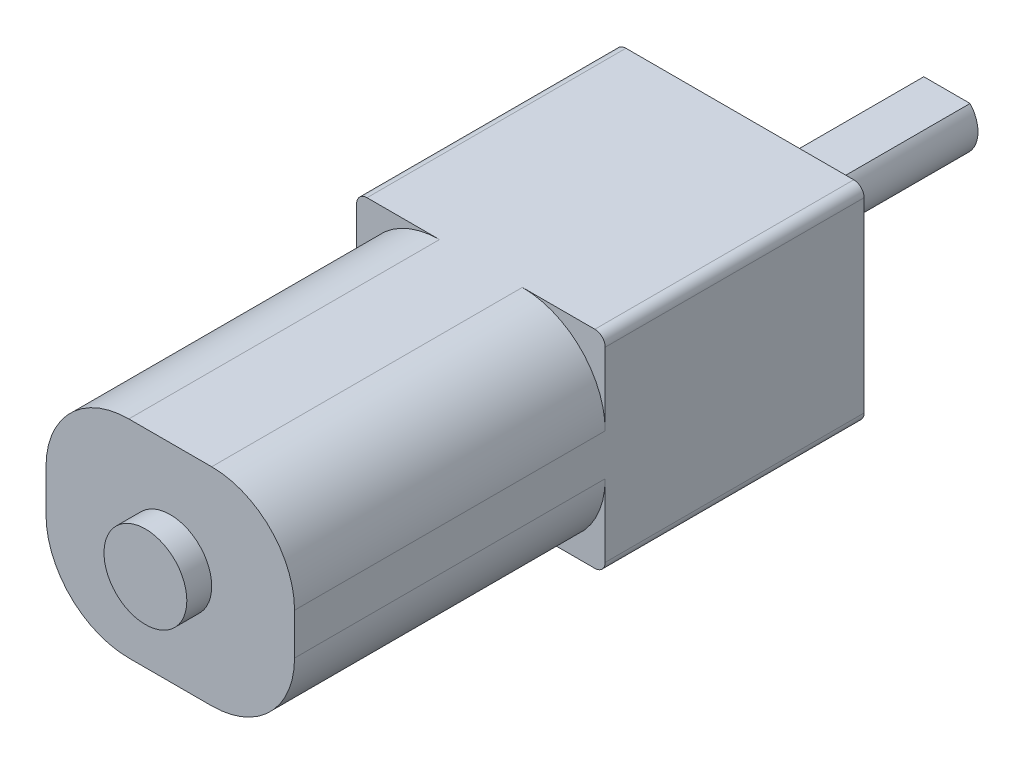
SolidWorks part; units mm, degrees
ref_plane "Front Plane" through (0, 0, 0) normal (0, 0, 1) x (1, 0, 0)
ref_plane "Top Plane" through (0, 0, 0) normal (0, 1, 0) x (1, 0, 0)
ref_plane "Right Plane" through (0, 0, 0) normal (1, 0, 0) x (0, 0, -1)
sketch "Sketch1" plane through (0, 0, 0) normal (0, 0, 1) x (1, 0, 0)
  line L1 (0, 0) -> (12, 0)
  line L2 (0, 0) -> (0, 10)
  line L3 (0, 10) -> (12, 10)
  line L4 (12, 0) -> (12, 10)
  dimension "D1" = 12
  dimension "D2" = 10
extrude "Boss-Extrude1" add sketch "Sketch1" along normal blind 15
fillet "Fillet1" radius 4 4 edges at (0, 0, 7.5) (0, 10, 7.5) (12, 0, 7.5) (12, 10, 7.5)
sketch "Sketch3" plane through (0, 0, 0) normal (0, 0, 1) x (1, 0, 0)
  line L1 (0, 0) -> (12, 0)
  line L2 (0, 0) -> (0, 10)
  line L3 (0, 10) -> (12, 10)
  line L4 (12, 0) -> (12, 10)
  dimension "D1" = 12
  dimension "D2" = 10
extrude "Boss-Extrude2" add sketch "Sketch3" against normal blind 12.5
sketch "Sketch4" plane through (0, 0, -12.5) normal (0, 0, -1) x (-1, 0, 0)
  line L0 (0, 0) -> (-12, 0) construction
  line L1 (0, 10) -> (0, 0) construction
  circle A0 centre (-6, 5) radius 2
  dimension "D1" = 4
  dimension "D3" = 6
  dimension "D2" = 5
extrude "Boss-Extrude3" add sketch "Sketch4" along normal blind 0.7
sketch "Sketch5" plane through (0, 0, -13.2) normal (0, 0, -1) x (-1, 0, 0)
  line L0 (-7.118, 6) -> (-4.882, 6)
  arc A0 (-7.118, 6) -> (-4.882, 6) centre (-6, 5) ccw
  dimension "D1" = 3
  dimension "D2" = 1
extrude "Boss-Extrude4" add sketch "Sketch5" along normal blind 9.3
sketch "Sketch7" plane through (0, 0, -12.5) normal (0, 0, -1) x (-1, 0, 0)
  line L0 (0, 0) -> (-12, 0) construction
  circle A0 centre (-10.5, 5) radius 0.8
  circle A1 centre (-1.5, 5) radius 0.8
  circle A2 centre (-6, 5) radius 2 construction
  dimension "D1" = 1.6
  dimension "D2" = 1.6
  dimension "D3" = 4.5
  dimension "D4" = 4.5
  dimension "D5" = 5
  dimension "D6" = 5
extrude "Cut-Extrude1" cut sketch "Sketch7" against normal blind 2
sketch "Sketch8" plane through (0, 0, 15) normal (0, 0, 1) x (1, 0, 0)
  line L0 (0, 6) -> (0, 4) construction
  line L1 (4, 0) -> (8, 0) construction
  circle A0 centre (6, 5) radius 2
  dimension "D1" = 4
  dimension "D2" = 6
  dimension "D3" = 5
extrude "Boss-Extrude5" add sketch "Sketch8" along normal blind 1.2
sketch "Sketch9" plane through (0, 0, 16.2) normal (0, 0, 1) x (1, 0, 0)
  circle A0 centre (6, 5) radius 0.6
  dimension "D1" = 1.2
fillet "Fillet2" radius 0.5 4 edges at (12, 0, -6.25) (0, 0, -6.25) (0, 10, -6.25) (12, 10, -6.25)
